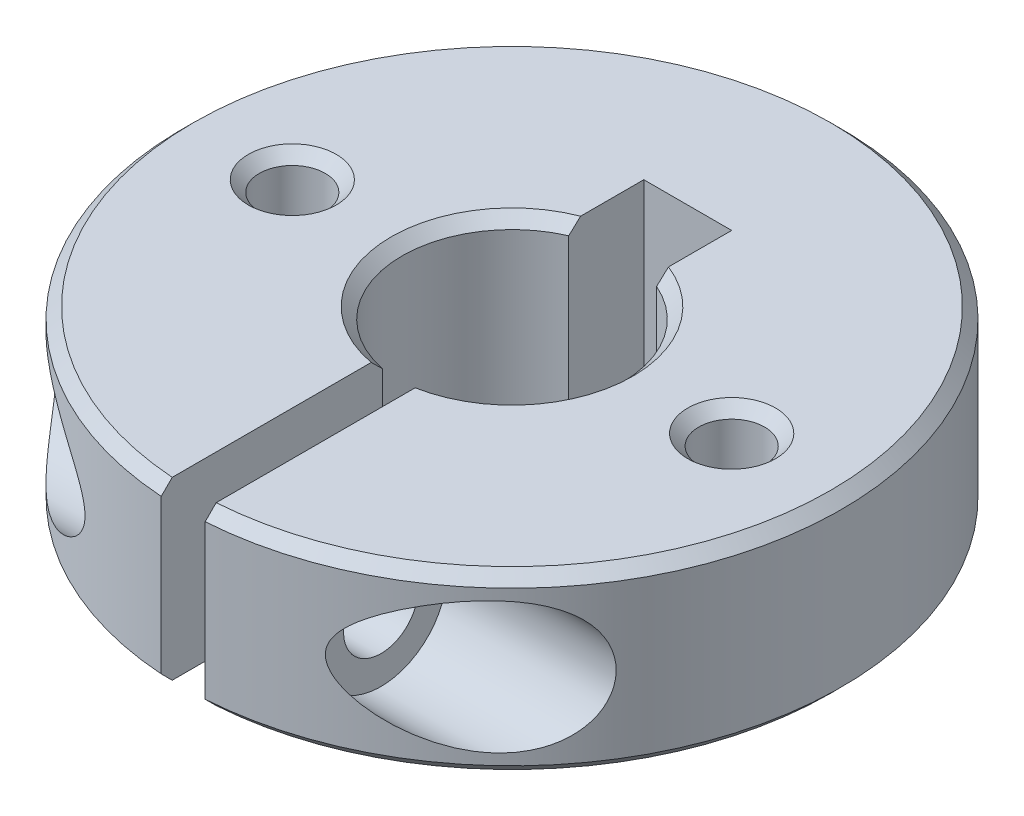
SolidWorks part; units mm, degrees
material "合金钢"
ref_plane "前视基准面" through (0, 0, 0) normal (0, 0, 1) x (1, 0, 0)
ref_plane "上视基准面" through (0, 0, 0) normal (0, 1, 0) x (1, 0, 0)
ref_plane "右视基准面" through (0, 0, 0) normal (1, 0, 0) x (0, 0, -1)
sketch "草图1" plane through (0, 0, 0) normal (0, 1, 0) x (1, 0, 0)
  circle A0 centre (0, 0) radius 15
  circle A1 centre (0, 0) radius 5
  dimension "D1" = 30
  dimension "D2" = 10
extrude "凸台-拉伸1" add sketch "草图1" along normal blind 8
sketch "草图2" plane through (0, 8, 0) normal (0, 1, 0) x (1, 0, 0)
  line L1 (-2, 4) -> (2, 4)
  line L2 (-2, 4) -> (-2, 8)
  line L3 (-2, 8) -> (2, 8)
  line L4 (2, 4) -> (2, 8)
  line L5 (-2, 4) -> (2, 8) construction
  line L6 (-2, 8) -> (2, 4) construction
  point P0 (0, 6)
  dimension "D1" = 4
  dimension "D2" = 8
  dimension "D3" = 4
extrude "切除-拉伸1" cut sketch "草图2" against normal through all
sketch "草图3" plane through (0, 8, 0) normal (0, 1, 0) x (1, 0, 0)
  line L1 (-1, 5) -> (1, 5)
  line L2 (-1, 5) -> (-1, -15)
  line L3 (-1, -15) -> (1, -15)
  line L4 (1, 5) -> (1, -15)
  line L5 (-1, 5) -> (1, -15) construction
  line L6 (-1, -15) -> (1, 5) construction
  arc A0 (-2, 4.5826) -> (2, 4.5826) centre (0, 0) ccw construction
  point P0 (0, -5)
  dimension "D1" = 2
  dimension "D2" = 20
extrude "切除-拉伸2" cut sketch "草图3" against normal through all
sketch "草图4" plane through (0, 0, 0) normal (1, 0, 0) x (0, 0, -1)
  line L0 (-14.9666, 8) -> (-14.9666, 0) construction
  circle A0 centre (-10.9666, 4) radius 1.7
  dimension "D2" = 3.4
  dimension "D1" = 4
extrude "切除-拉伸3" cut sketch "草图4" against normal through all both and the other way through all
ref_plane "基准面1" through (15, 0, 0) normal (1, 0, 0) x (0, 0, -1)
sketch "草图5" plane through (15, 0, 0) normal (1, 0, 0) x (0, 0, -1)
  circle A0 centre (-10.9666, 4) radius 3
  dimension "D1" = 6
extrude "切除-拉伸4" cut sketch "草图5" against normal blind 10
mirror "镜向1" about plane through (0, 0, 0) normal (1, 0, 0) of "切除-拉伸4"
sketch "草图6" plane through (0, 8, 0) normal (0, 1, 0) x (1, 0, 0)
  line L0 (0, 13.4005) -> (0, -13.3945) construction
  circle A0 centre (0, 0) radius 10 construction
  circle A1 centre (10, 0) radius 1.5
  circle A2 centre (-10, 0) radius 1.5
  dimension "D1" = 20
  dimension "D2" = 3
extrude "切除-拉伸5" cut sketch "草图6" against normal through all
chamfer "倒角1" distance 0.5 angle 45 10 edges at (4.9724, 0, 0.5244) (-4.9724, 8, 0.5244) (0, 0, -15) (0, 8, -15) (10, 0, 1.5) (-10, 0, -1.5) (-10, 8, -1.5) (10, 8, 1.5) (-4.9724, 0, 0.5244) (4.9724, 8, 0.5244)
